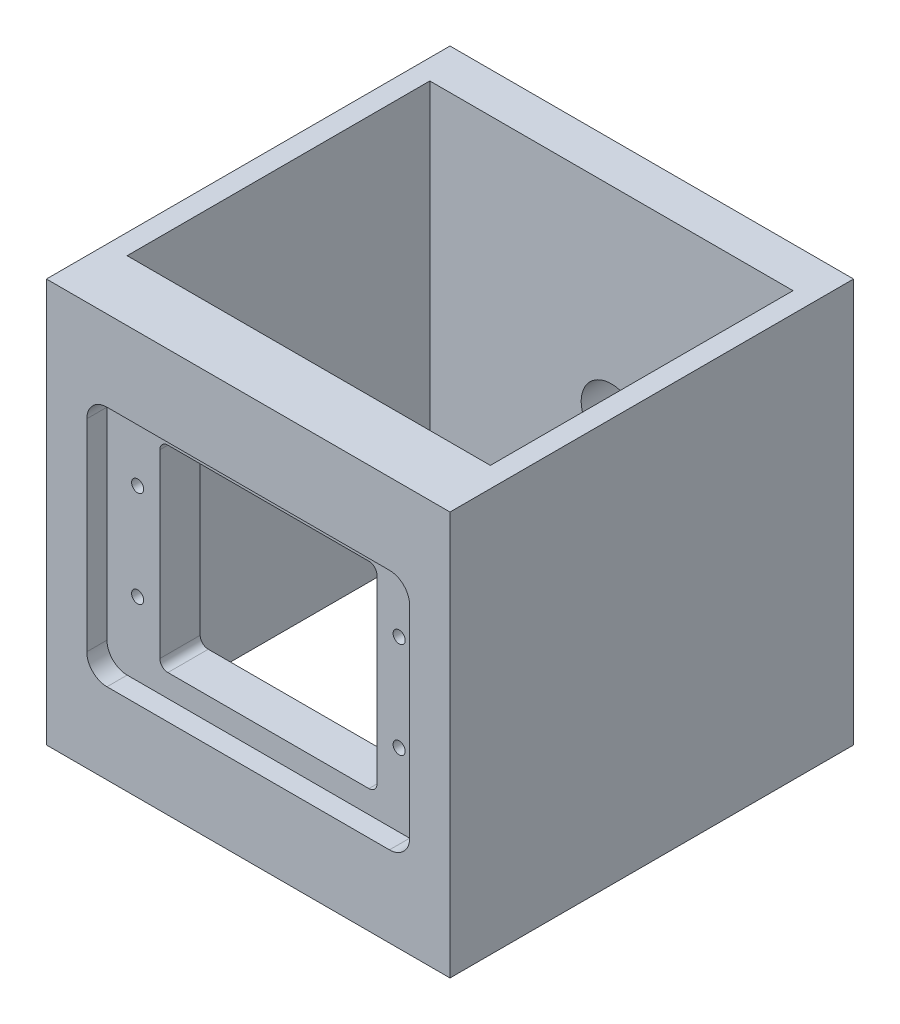
SolidWorks part; units mm, degrees
ref_plane "前基準面" through (0, 0, 0) normal (0, 0, 1) x (1, 0, 0)
ref_plane "上基準面" through (0, 0, 0) normal (0, 1, 0) x (1, 0, 0)
ref_plane "右基準面" through (0, 0, 0) normal (1, 0, 0) x (0, 0, -1)
sketch "草圖1" plane through (0, 0, 0) normal (0, 0, 1) x (1, 0, 0)
  line L1 (-50, 50) -> (50, 50)
  line L2 (-50, 50) -> (-50, -50)
  line L3 (-50, -50) -> (50, -50)
  line L4 (50, 50) -> (50, -50)
  line L5 (-50, 50) -> (50, -50) construction
  line L6 (-50, -50) -> (50, 50) construction
  point P0 (0, 0)
  dimension "D1" = 100
  dimension "D2" = 100
extrude "填料-伸長1" add sketch "草圖1" along normal blind 100
sketch "草圖2" plane through (0, -50, 0) normal (0, -1, 0) x (1, 0, 0)
  line L0 (-50, 0) -> (50, 0) construction
  line L1 (-45, 85) -> (45, 85)
  line L2 (-45, 85) -> (-45, 10)
  line L3 (-45, 10) -> (45, 10)
  line L4 (45, 85) -> (45, 10)
  line L5 (-45, 85) -> (45, 10) construction
  line L6 (-45, 10) -> (45, 85) construction
  line L7 (-50, 100) -> (50, 100) construction
  line L8 (-50, 100) -> (-50, 0) construction
  line L9 (50, 100) -> (50, 0) construction
  point P0 (0, 47.5)
  dimension "D1" = 10
  dimension "D2" = 15
  dimension "D3" = 5
  dimension "D4" = 5
extrude "除料-伸長1" cut sketch "草圖2" against normal through all
sketch "草圖3" plane through (0, 0, 0) normal (0, 0, -1) x (-1, 0, 0)
  circle A0 centre (0, 0) radius 7.5
  dimension "D1" = 15
extrude "除料-伸長2" cut sketch "草圖3" against normal up to next
sketch "草圖4" plane through (0, 0, 85) normal (0, 0, -1) x (-1, 0, 0)
  line L0 (0, 26.9) -> (0, -26.9) construction
  line L1 (-34.9, 26.9) -> (34.9, 26.9) construction
  line L2 (-34.9, 26.9) -> (-34.9, -26.9) construction
  line L3 (-34.9, -26.9) -> (34.9, -26.9) construction
  line L4 (34.9, 26.9) -> (34.9, -26.9) construction
  line L5 (-34.9, 26.9) -> (34.9, -26.9) construction
  line L6 (-34.9, -26.9) -> (34.9, 26.9) construction
  line L7 (34.9, 0) -> (-34.9, 0) construction
  line L8 (24.9, 24.4) -> (-24.9, 24.4)
  line L9 (26.9, 22.4) -> (26.9, -22.4)
  line L10 (24.9, -24.4) -> (-24.9, -24.4)
  line L11 (-26.9, 22.4) -> (-26.9, -22.4)
  line L12 (26.9, 24.4) -> (-26.9, -24.4) construction
  line L13 (26.9, -24.4) -> (-26.9, 24.4) construction
  circle A0 centre (21.9, 19.4) radius 4 construction
  circle A1 centre (-21.9, 19.4) radius 4 construction
  circle A2 centre (21.9, -19.4) radius 4 construction
  arc A3 (26.9, -22.4) -> (24.9, -24.4) centre (24.9, -22.4) cw
  arc A4 (-24.9, -24.4) -> (-26.9, -22.4) centre (-24.9, -22.4) cw
  arc A5 (-24.9, 24.4) -> (-26.9, 22.4) centre (-24.9, 22.4) ccw
  arc A6 (24.9, 24.4) -> (26.9, 22.4) centre (24.9, 22.4) cw
  circle A7 centre (-32.4, 11.9) radius 1.5
  circle A8 centre (32.4, 11.9) radius 1.5
  circle A9 centre (32.4, -11.9) radius 1.5
  circle A10 centre (-32.4, -11.9) radius 1.5
  point P0 (0, 0)
  point P12 (0, 0)
  dimension "D3" = 8
  dimension "D8" = 2
  dimension "D11" = 3
  dimension "D1" = 69.8
  dimension "D2" = 53.8
  dimension "D4" = 13
  dimension "D5" = 7.5
  dimension "D6" = 5
  dimension "D7" = 5
  dimension "D9" = 2.5
  dimension "D10" = 15
extrude "除料-伸長3" cut sketch "草圖4" against normal up to next
sketch "草圖5" plane through (0, 0, 100) normal (0, 0, 1) x (1, 0, 0)
  line L1 (-35, 30) -> (35, 30)
  line L2 (-40, 25) -> (-40, -25)
  line L3 (-35, -30) -> (35, -30)
  line L4 (40, 25) -> (40, -25)
  line L5 (-40, 30) -> (40, -30) construction
  line L6 (-40, -30) -> (40, 30) construction
  arc A0 (-40, -25) -> (-35, -30) centre (-35, -25) ccw
  arc A1 (35, -30) -> (40, -25) centre (35, -25) ccw
  arc A2 (35, 30) -> (40, 25) centre (35, 25) cw
  arc A3 (-35, 30) -> (-40, 25) centre (-35, 25) ccw
  point P0 (0, 0)
  dimension "D3" = 5
  dimension "D1" = 80
  dimension "D2" = 60
extrude "除料-伸長4" cut sketch "草圖5" against normal blind 5
sketch "草圖6" plane through (0, 0, 85) normal (0, 0, -1) x (-1, 0, 0)
  line L0 (-50, 0) -> (50, 0) construction
  line L1 (-35.2399, 21) -> (-29.2399, 21)
  line L2 (-35.2399, 21) -> (-35.2399, -21)
  line L3 (-35.2399, -21) -> (-29.2399, -21)
  line L4 (-29.2399, 21) -> (-29.2399, -21)
  line L5 (-35.2399, 21) -> (-29.2399, -21) construction
  line L6 (-35.2399, -21) -> (-29.2399, 21) construction
  line L7 (-50, -50) -> (-50, 50) construction
  line L8 (50, 50) -> (50, -50) construction
  line L9 (0, 50) -> (0, -50) construction
  line L10 (-45, 50) -> (45, 50) construction
  line L11 (-45, -50) -> (45, -50) construction
  line L12 (35.2399, -21) -> (29.2399, -21)
  line L13 (35.2399, 21) -> (29.2399, -21) construction
  line L14 (35.2399, -21) -> (29.2399, 21) construction
  line L15 (29.2399, 21) -> (29.2399, -21)
  line L16 (35.2399, 21) -> (35.2399, -21)
  line L17 (35.2399, 21) -> (29.2399, 21)
  circle A0 centre (-32.2399, 21) radius 3
  circle A1 centre (-32.2399, -21) radius 3
  circle A2 centre (32.2399, -21) radius 3
  circle A3 centre (32.2399, 21) radius 3
  point P0 (-32.2399, 0)
  circle M5 centre (-32.4, -11.9) radius 1.5
  circle M6 centre (32.4, -11.9) radius 1.5
  circle M7 centre (32.4, 11.9) radius 1.5
  circle M8 centre (-32.4, 11.9) radius 1.5
  dimension "D1" = 32.2399
  dimension "D2" = 21
  dimension "D3" = 6
extrude "除料-伸長5" cut sketch "草圖6" against normal blind 5 contours L1 A0 | L1 A0 | A1 L4 A0 L2 M8 M5 | L3 A1 | L3 A1 | A3 L17 | A3 L17 | L16 A3 L15 A2 M6 M7 | A2 L12 | A2 L12
